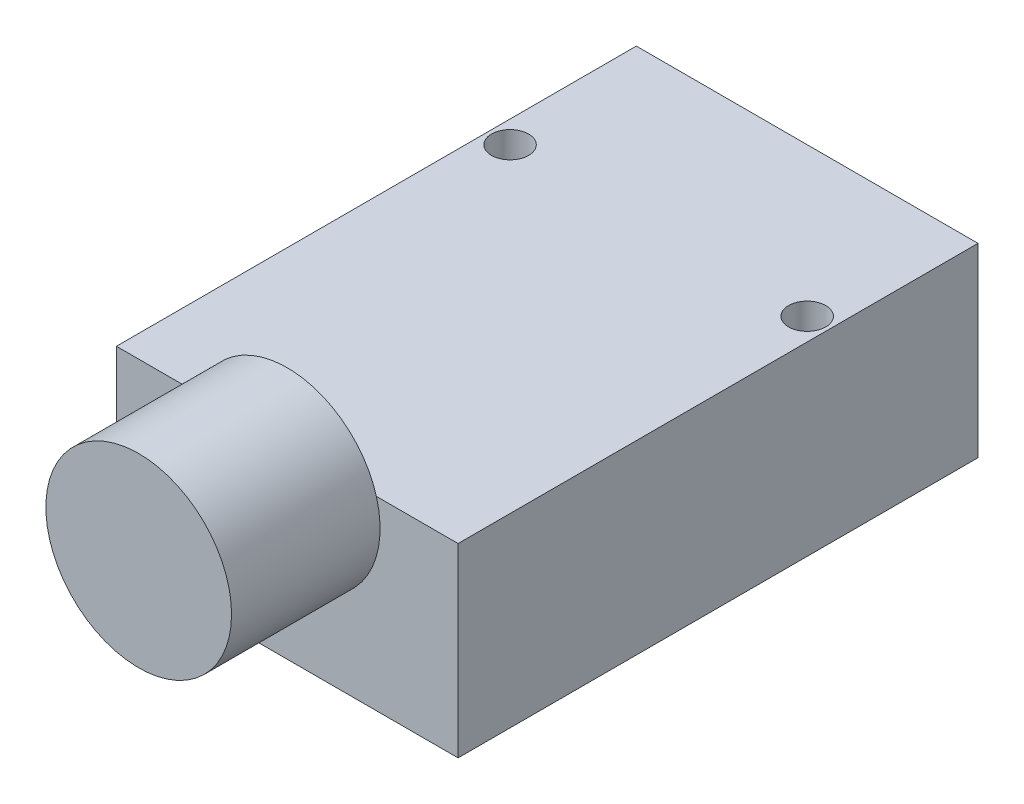
SolidWorks part; units mm, degrees
ref_plane "Front Plane" through (0, 0, 0) normal (0, 0, 1) x (1, 0, 0)
ref_plane "Top Plane" through (0, 0, 0) normal (0, 1, 0) x (1, 0, 0)
ref_plane "Right Plane" through (0, 0, 0) normal (1, 0, 0) x (0, 0, -1)
sketch "Sketch1" plane through (0, 0, 0) normal (0, 1, 0) x (1, 0, 0)
  line L1 (0, 0) -> (46, 0)
  line L2 (0, 0) -> (0, 70)
  line L3 (0, 70) -> (46, 70)
  line L4 (46, 0) -> (46, 70)
  dimension "D1" = 46
  dimension "D2" = 70
extrude "Boss-Extrude1" add sketch "Sketch1" along normal blind 25
sketch "Sketch2" plane through (0, 0, 0) normal (0, 0, 1) x (1, 0, 0)
  line L0 (23, 25) -> (23, 0) construction
  line L1 (0, 25) -> (46, 25) construction
  line L2 (0, 0) -> (46, 0) construction
  circle A0 centre (23, 21.5) radius 12.5
  point P8 (0, 0)
  point P9 (23, 34)
  dimension "D1" = 25
  dimension "D2" = 34
extrude "Boss-Extrude2" add sketch "Sketch2" along normal blind 20
sketch "Sketch3" plane through (0, 25, 0) normal (0, 1, 0) x (1, 0, 0)
  line L0 (43, 50) -> (3, 50) construction
  line L1 (23, 50) -> (23, 70) construction
  line L2 (46, 70) -> (0, 70) construction
  line L3 (46, 0) -> (46, 70) construction
  circle A0 centre (3, 50) radius 2.5
  circle A1 centre (43, 50) radius 2.5
  dimension "D1" = 5
  dimension "D2" = 40
  dimension "D3" = 20
extrude "Cut-Extrude1" cut sketch "Sketch3" against normal up to next
